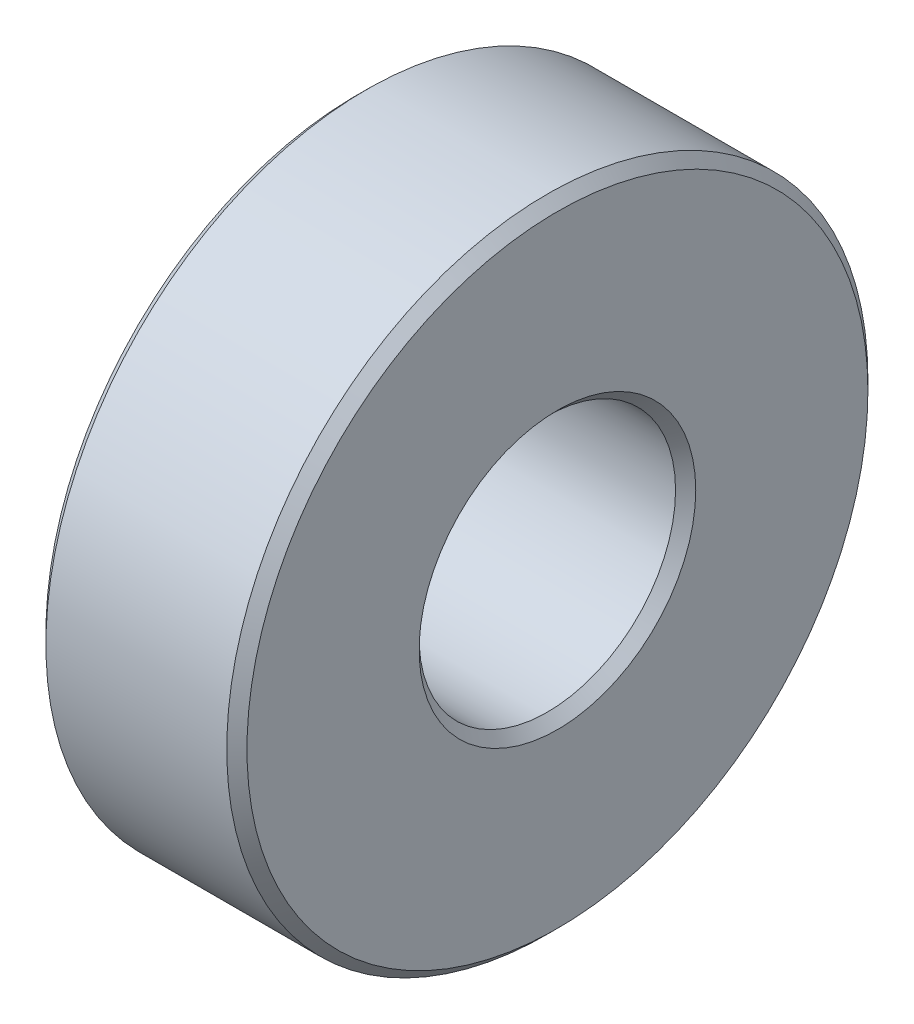
SolidWorks part; units mm, degrees
ref_plane "Front Plane" through (0, 0, 0) normal (0, 0, 1) x (1, 0, 0)
ref_plane "Top Plane" through (0, 0, 0) normal (0, 1, 0) x (1, 0, 0)
ref_plane "Right Plane" through (0, 0, 0) normal (1, 0, 0) x (0, 0, -1)
sketch "Sketch1" plane through (0, 0, 0) normal (1, 0, 0) x (0, 0, -1)
  circle A0 centre (0, 0) radius 7.9375
  circle A1 centre (0, 0) radius 3.175
  dimension "D1" = 15.875
  dimension "D2" = 6.35
extrude "Boss-Extrude1" add sketch "Sketch1" along normal mid plane 4.978
chamfer "Chamfer1" distance 0.25 angle 45 3 edges at (2.489, 0, -3.175) (-2.489, 0, -7.9375) (2.489, 0, -7.9375)
